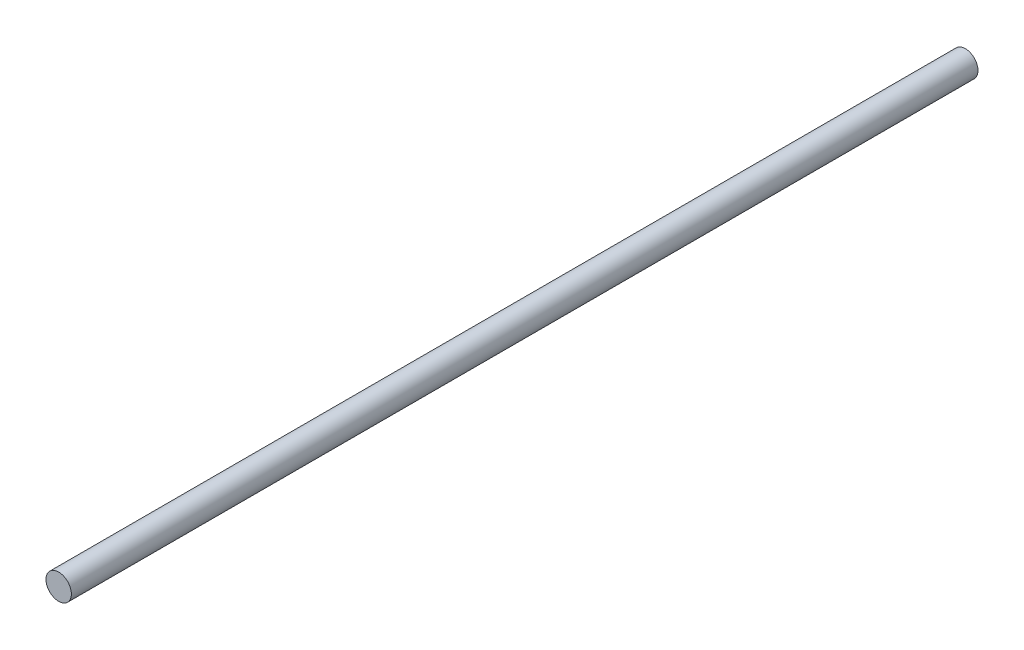
SolidWorks part; units mm, degrees
ref_plane "Front Plane" through (0, 0, 0) normal (0, 0, 1) x (1, 0, 0)
ref_plane "Top Plane" through (0, 0, 0) normal (0, 1, 0) x (1, 0, 0)
ref_plane "Right Plane" through (0, 0, 0) normal (1, 0, 0) x (0, 0, -1)
sketch "Sketch1" plane through (0, 0, 0) normal (0, 0, 1) x (1, 0, 0)
  circle A0 centre (0, 0) radius 3.5
  dimension "D1" = 7
extrude "Boss-Extrude1" add sketch "Sketch1" along normal blind 250 contours A0
